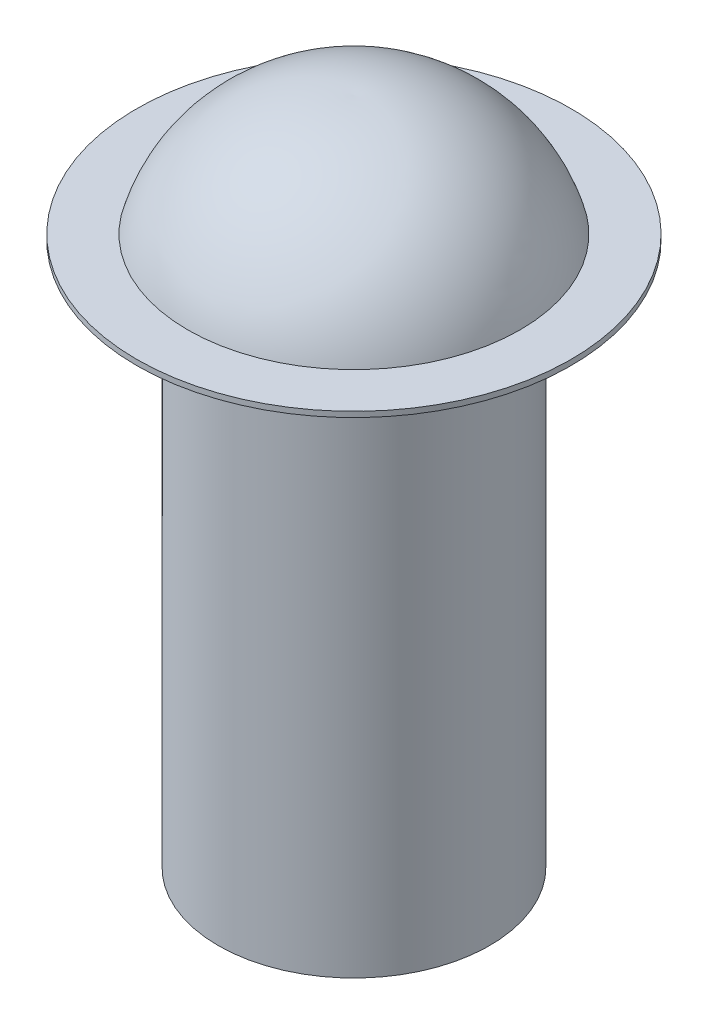
SolidWorks part; units mm, degrees
ref_plane "Front Plane" through (0, 0, 0) normal (0, 0, 1) x (1, 0, 0)
ref_plane "Top Plane" through (0, 0, 0) normal (0, 1, 0) x (1, 0, 0)
ref_plane "Right Plane" through (0, 0, 0) normal (1, 0, 0) x (0, 0, -1)
sketch "Sketch1" plane through (0, 0, 0) normal (0, 1, 0) x (1, 0, 0)
  circle A0 centre (0, 0) radius 3.175
  dimension "D1" = 6.35
extrude "Boss-Extrude1" add sketch "Sketch1" along normal blind 12.7
sketch "Sketch2" plane through (0, 12.7, 0) normal (0, 1, 0) x (1, 0, 0)
  circle A0 centre (0, 0) radius 5.08
  circle A1 centre (0, 0) radius 3.175 construction
  dimension "D1" = 10.16
extrude "Boss-Extrude2" add sketch "Sketch2" along normal blind 0.127
sketch "Sketch3" plane through (0, 0, 0) normal (0, 0, 1) x (1, 0, 0)
  line L0 (0, 12.827) -> (-3.8863, 12.827)
  line L1 (5.08, 12.827) -> (-5.08, 12.827) construction
  line L2 (0, 12.827) -> (0, 15.6476)
  arc A0 (-3.8863, 12.827) -> (0, 15.6476) centre (-0.1666, 11.7894) cw
  point P7 (-3.9001, 12.827)
  point P8 (0, 15.6476)
  dimension "D1" = 3.8618
  dimension "D2" = 0.1666
  dimension "D3" = 3.8863
revolve "Revolve1" add sketch "Sketch3" angle 360 about L2
